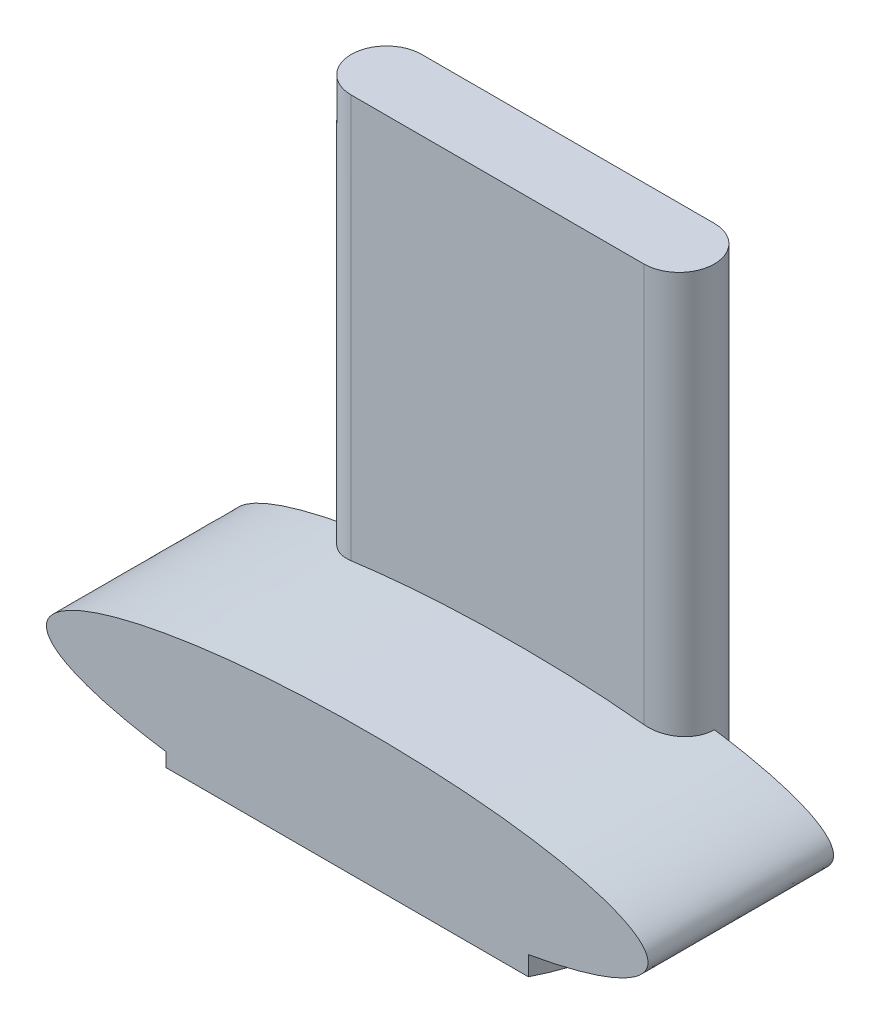
SolidWorks part; units mm, degrees
ref_plane "Front Plane" through (0, 0, 0) normal (0, 0, 1) x (1, 0, 0)
ref_plane "Top Plane" through (0, 0, 0) normal (0, 1, 0) x (1, 0, 0)
ref_plane "Right Plane" through (0, 0, 0) normal (1, 0, 0) x (0, 0, -1)
sketch "Sketch2" plane through (0, 0, 0) normal (0, 0, 1) x (1, 0, 0)
  ellipse E0 centre (-67.8024, 6.5713) end of major axis (-20.8024, 7.3168) minor radius 10.0013
  dimension "D2" = 20
  dimension "D1" = 94
extrude "Boss-Extrude2" add sketch "Sketch2" along normal blind 29
sketch "Sketch3" plane through (0, 0, 0) normal (0, 1, 0) x (1, 0, 0)
  line L0 (-96.1084, -29) -> (-39.4964, -29)
  line L1 (-114.8026, -29) -> (-20.8021, -29) construction
  line L2 (-39.4964, 0) -> (-96.1084, 0)
  line L3 (-20.8021, 0) -> (-114.8026, 0) construction
  arc A0 (-39.4964, -29) -> (-39.4964, 0) centre (-67.8024, -14.5) ccw
  arc A1 (-96.1084, 0) -> (-96.1084, -29) centre (-67.8024, -14.5) ccw
  dimension "D1" = 31.8038
extrude "Boss-Extrude3" add sketch "Sketch3" against normal blind 4
ref_plane "Plane1" through (0, 8, 0) normal (0, -1, 0) x (-1, 0, 0)
sketch "Sketch5" plane through (0, 8, 0) normal (0, -1, 0) x (-1, 0, 0)
  line L0 (44.9321, 0) -> (90.6726, 0) construction
  line L1 (44.9321, 5.4997) -> (90.6726, 5.4997)
  line L2 (44.9321, -5.4997) -> (90.6726, -5.4997)
  line L3 (20.8021, 0) -> (20.8021, -29) construction
  line L5 (114.8026, -29) -> (114.8026, 0) construction
  arc A0 (44.9321, 5.4997) -> (44.9321, -5.4997) centre (44.9321, 0) ccw
  arc A1 (90.6726, -5.4997) -> (90.6726, 5.4997) centre (90.6726, 0) ccw
  point P3 (67.8024, 0)
  dimension "D1" = 24.13
  dimension "D2" = 24.13
extrude "Boss-Extrude4" add sketch "Sketch5" against normal blind 70
